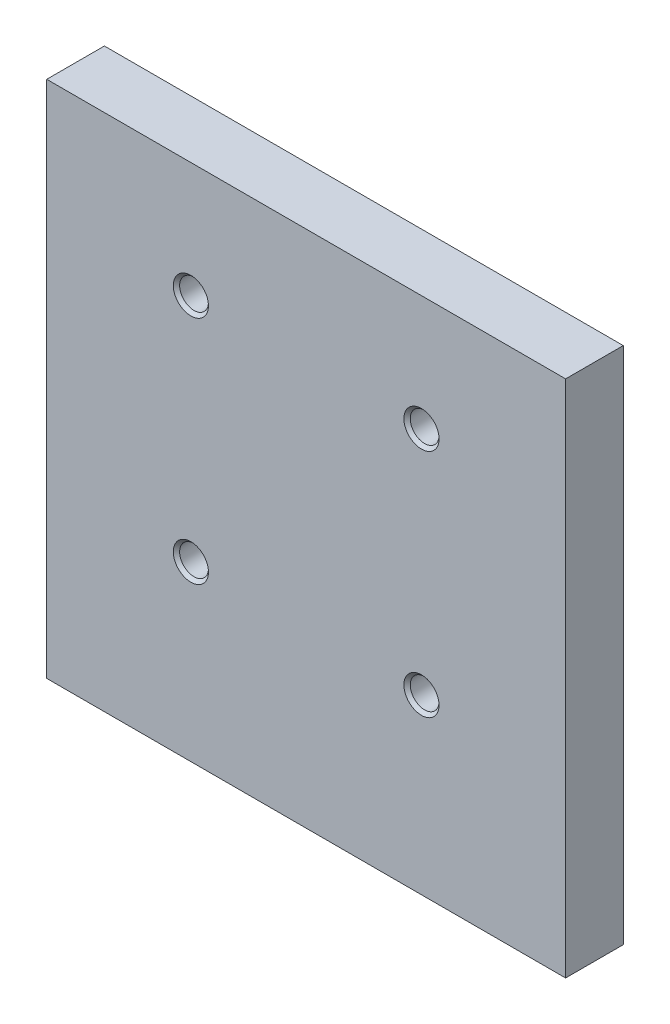
SolidWorks part; units mm, degrees
ref_plane "前视基准面" through (0, 0, 0) normal (0, 0, 1) x (1, 0, 0)
ref_plane "上视基准面" through (0, 0, 0) normal (0, 1, 0) x (1, 0, 0)
ref_plane "右视基准面" through (0, 0, 0) normal (1, 0, 0) x (0, 0, -1)
other "Configuration Table"
sketch "草图1" plane through (0, 0, 0) normal (0, 0, 1) x (1, 0, 0)
  line L0 (22.5, 45) -> (22.5, 0) construction
  line L1 (0, 0) -> (45, 0)
  line L2 (0, 0) -> (0, 45)
  line L3 (0, 45) -> (45, 45)
  line L4 (45, 0) -> (45, 45)
  circle A0 centre (12.5, 35) radius 1.6 construction
  circle A1 centre (32.5, 35) radius 1.6 construction
  circle A2 centre (32.5, 15) radius 1.6 construction
  circle A3 centre (12.5, 15) radius 1.6 construction
  point P14 (12.5, 35)
  dimension "D7" = 3.2
  dimension "D1" = 45
  dimension "D2" = 45
  dimension "D3" = 10
  dimension "D4" = 20
  dimension "D5" = 10
  dimension "D6" = 20
extrude "凸台-拉伸1" add sketch "草图1" along normal blind 5
sketch "草图2" plane through (0, 0, 5) normal (0, 0, 1) x (1, 0, 0)
  line L0 (22.5, 0) -> (22.5, 45) construction
  line L1 (0, 0) -> (45, 0) construction
  line L2 (45, 45) -> (0, 45) construction
  point P0 (12.5, 35)
  point P1 (32.5, 35)
  point P2 (32.5, 15)
  point P4 (12.5, 15)
  dimension "D1" = 10
  dimension "D2" = 10
  dimension "D3" = 10
  dimension "D4" = 10
  dimension "D5" = 20
  dimension "D6" = 10
  dimension "D7" = 30
  dimension "D8" = 10
hole_wizard "M3 螺纹孔3" positions "草图2" profile "草图7" tap size "M3" standard "GB" end condition through all
sketch "草图7" plane through (12.5, 35, 5) normal (1, 0, 0) x (0, -1, 0)
  line L0 (0, 0) -> (0, 5)
  line L1 (0, 5) -> (1.25, 5)
  line L2 (1.25, 5) -> (1.25, 0.275)
  line L3 (1.25, 0.275) -> (1.525, 0)
  line L5 (1.525, 0) -> (0, 0)
  line L6 (-1.25, 0.275) -> (-1.525, 0) construction
  line L11 (0, -6.35) -> (0, 107.95) construction
  dimension "通孔螺纹孔钻头直径" = 2.5
  dimension "通孔螺纹孔钻头深度" = 5
  dimension "近端锥形沉头孔直径" = 3.05
  dimension "近端锥形沉头孔角度" = 90
cosmetic thread "孔螺纹线1" parameters "D2"=3
cosmetic thread "孔螺纹线2" parameters "D2"=3
cosmetic thread "孔螺纹线3" parameters "D2"=3
cosmetic thread "孔螺纹线4" parameters "D2"=3
